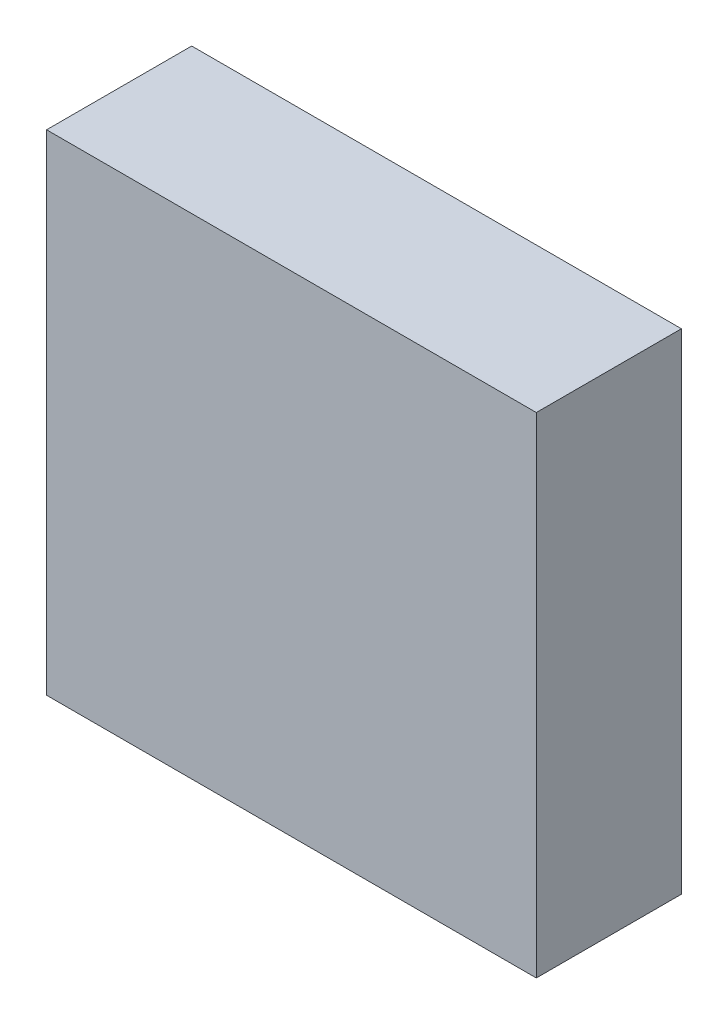
SolidWorks part; units mm, degrees
ref_plane "Front Plane" through (0, 0, 0) normal (0, 0, 1) x (1, 0, 0)
ref_plane "Top Plane" through (0, 0, 0) normal (0, 1, 0) x (1, 0, 0)
ref_plane "Right Plane" through (0, 0, 0) normal (1, 0, 0) x (0, 0, -1)
sketch "Sketch1" plane through (0, 0, 0) normal (0, 0, 1) x (1, 0, 0)
  line L1 (-85.725, 85.725) -> (85.725, 85.725)
  line L2 (-85.725, 85.725) -> (-85.725, -85.725)
  line L3 (-85.725, -85.725) -> (85.725, -85.725)
  line L4 (85.725, 85.725) -> (85.725, -85.725)
  line L5 (-85.725, 85.725) -> (85.725, -85.725) construction
  line L6 (-85.725, -85.725) -> (85.725, 85.725) construction
  point P0 (0, 0)
  dimension "D1" = 171.45
  dimension "D2" = 171.45
extrude "Boss-Extrude1" add sketch "Sketch1" along normal blind 50.8
